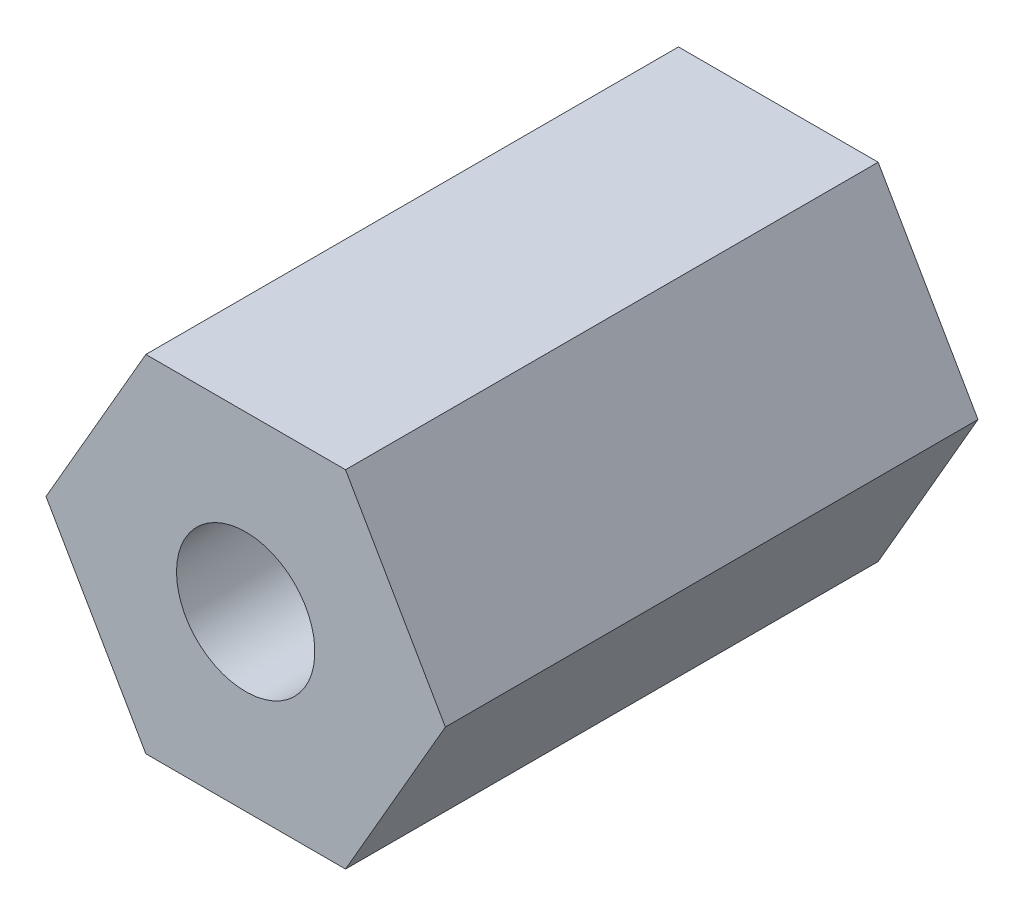
SolidWorks part; units mm, degrees
ref_plane "前视基准面" through (0, 0, 0) normal (0, 0, 1) x (1, 0, 0)
ref_plane "上视基准面" through (0, 0, 0) normal (0, 1, 0) x (1, 0, 0)
ref_plane "右视基准面" through (0, 0, 0) normal (1, 0, 0) x (0, 0, -1)
sketch "草图1" plane through (0, 0, 0) normal (0, 0, 1) x (1, 0, 0)
  line L1 (2.8868, -5) -> (5.7735, 0)
  line L2 (5.7735, 0) -> (2.8868, 5)
  line L3 (2.8868, 5) -> (-2.8868, 5)
  line L4 (-2.8868, 5) -> (-5.7735, 0)
  line L5 (-5.7735, 0) -> (-2.8868, -5)
  line L6 (-2.8868, -5) -> (2.8868, -5)
  circle A0 centre (0, 0) radius 2
  circle A1 centre (0, 0) radius 5 construction
  dimension "D1" = 4
  dimension "D2" = 10
extrude "凸台-拉伸1" add sketch "草图1" along normal blind 15.4
